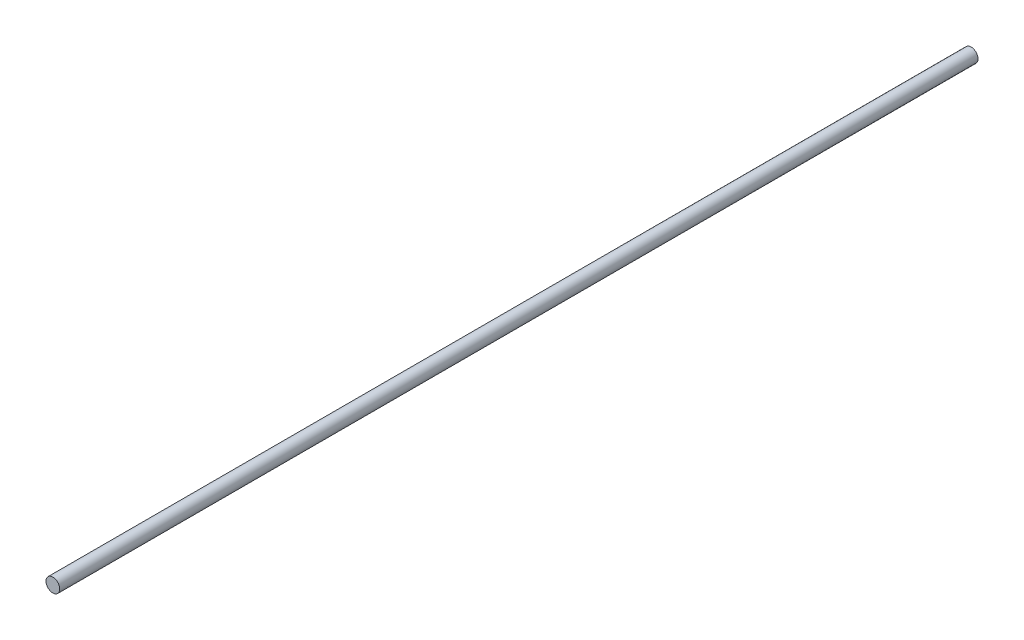
SolidWorks part; units mm, degrees
ref_plane "Plan de face" through (0, 0, 0) normal (0, 0, 1) x (1, 0, 0)
ref_plane "Plan de dessus" through (0, 0, 0) normal (0, 1, 0) x (1, 0, 0)
ref_plane "Plan de droite" through (0, 0, 0) normal (1, 0, 0) x (0, 0, -1)
sketch "Esquisse1" plane through (0, 0, 0) normal (0, 0, 1) x (1, 0, 0)
  circle A0 centre (0, 0) radius 3
  dimension "D1" = 6
extrude "Boss.-Extru.1" add sketch "Esquisse1" along normal blind 400 contours A0
